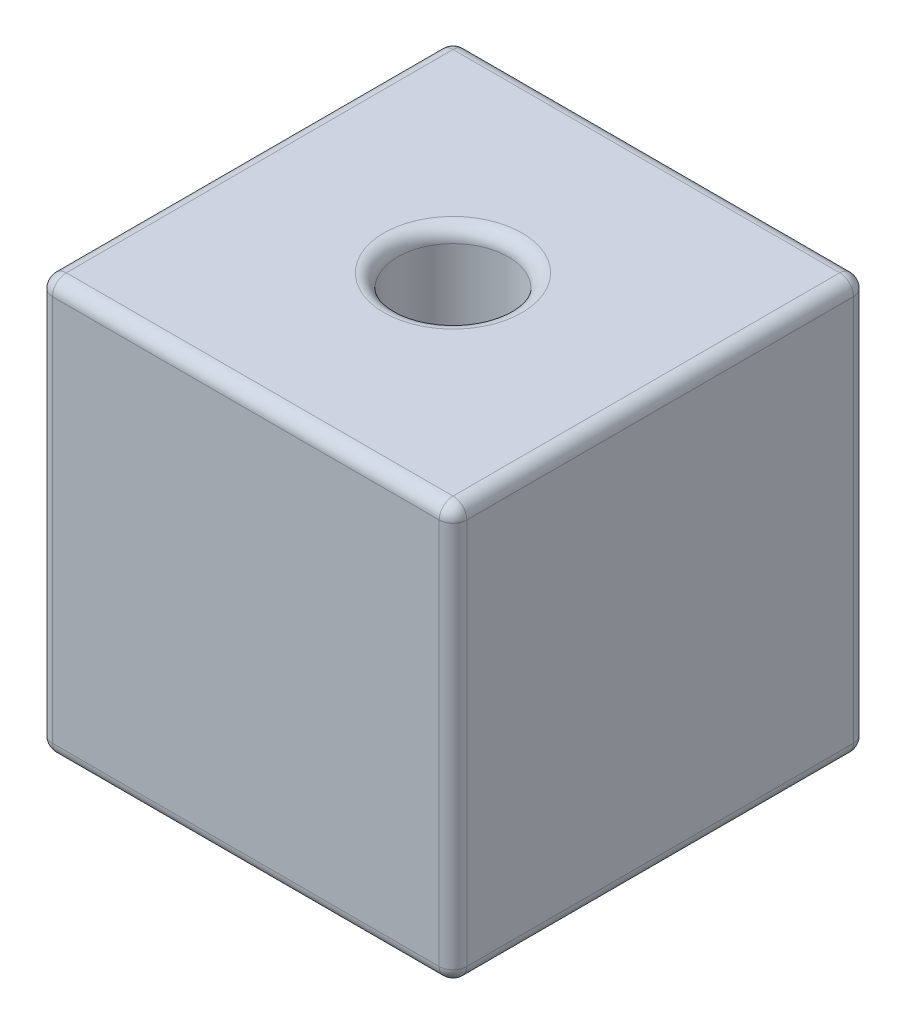
SolidWorks part; units mm, degrees
material "6061 Legierung"
ref_plane "Ebene vorne" through (0, 0, 0) normal (0, 0, 1) x (1, 0, 0)
ref_plane "Ebene oben" through (0, 0, 0) normal (0, 1, 0) x (1, 0, 0)
ref_plane "Ebene rechts" through (0, 0, 0) normal (1, 0, 0) x (0, 0, -1)
sketch "Skizze1" plane through (0, 0, 0) normal (0, 1, 0) x (1, 0, 0)
  line L1 (-15, 15) -> (15, 15)
  line L2 (-15, 15) -> (-15, -15)
  line L3 (-15, -15) -> (15, -15)
  line L4 (15, 15) -> (15, -15)
  line L5 (-15, 15) -> (15, -15) construction
  line L6 (-15, -15) -> (15, 15) construction
  point P0 (0, 0)
  dimension "D1" = 30
extrude "Aufsatz-Linear austragen1" add sketch "Skizze1" along normal blind 30
sketch "Skizze2" plane through (0, 30, 0) normal (0, 1, 0) x (1, 0, 0)
  line L0 (0, 15) -> (0, 0) construction
  line L1 (15, 15) -> (-15, 15) construction
  line L2 (0, 0) -> (0, -15) construction
  line L3 (-15, -15) -> (15, -15) construction
  line L4 (-15, 0) -> (0, 0) construction
  line L5 (-15, 15) -> (-15, -15) construction
  line L6 (0, 0) -> (15, 0) construction
  line L7 (15, -15) -> (15, 15) construction
  circle A0 centre (0, 0) radius 4
  dimension "D1" = 8
extrude "Schnitt-Linear austragen1" cut sketch "Skizze2" against normal blind 31
fillet "Verrundung1" radius 1 14 edges at (-15, 15, 15) (15, 15, 15) (15, 15, -15) (-15, 15, -15) (0, 0, -15) (-15, 0, 0) (0, 0, 15) (15, 0, 0) (0, 0, 4) (0, 30, 15) (-15, 30, 0) (0, 30, -15) (15, 30, 0) (0, 30, 4)
